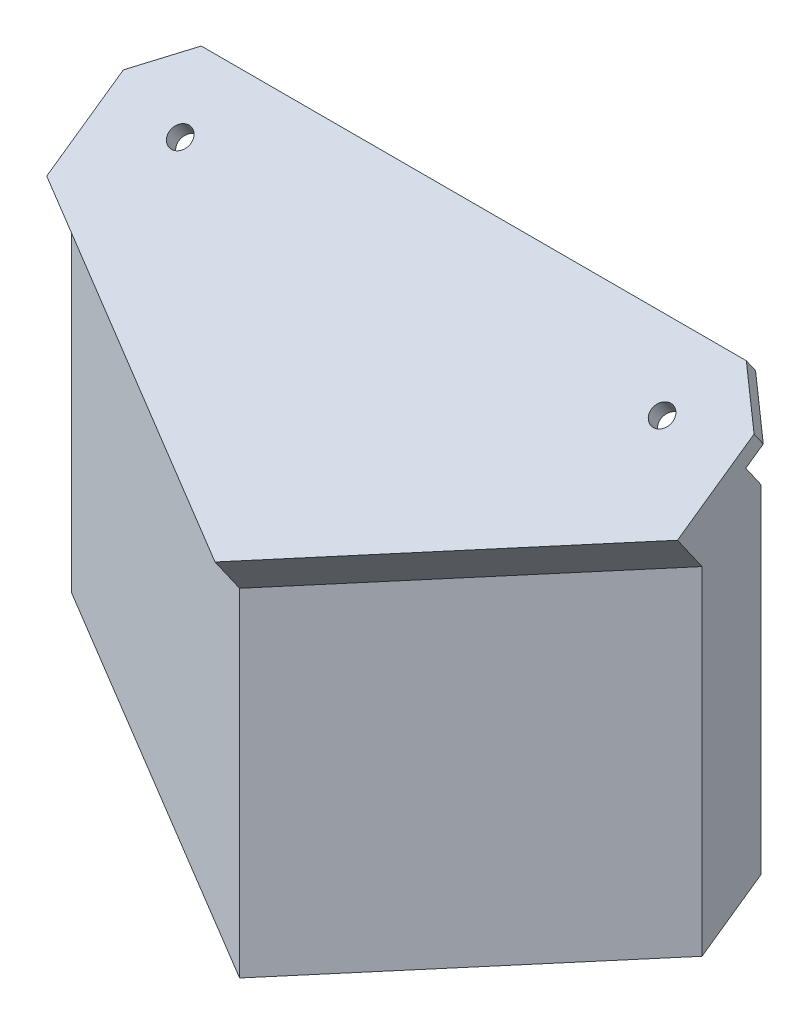
SolidWorks part; units mm, degrees
ref_plane "前视基准面" through (0, 0, 0) normal (0, 0, 1) x (1, 0, 0)
ref_plane "上视基准面" through (0, 0, 0) normal (0, 1, 0) x (1, 0, 0)
ref_plane "右视基准面" through (0, 0, 0) normal (1, 0, 0) x (0, 0, -1)
sketch "草图5" plane through (0, 0, 0) normal (0, 1, 0) x (1, 0, 0)
  line L0 (-58.91, 27.4702) -> (0, 0)
  line L1 (0, 0) -> (58.91, 27.4702)
  dimension "D1" = 65
  dimension "D2" = 130
extrude "拉伸-薄壁2" add sketch "草图5" along normal blind 90 thin
sketch "草图6" plane through (0, 0, 0) normal (1, 0, 0) x (0, 0, -1)
  line L0 (-11.0338, 0) -> (27.4702, 26.9608)
  line L1 (27.4702, 90) -> (27.4702, 0) construction
  line L2 (27.4702, 26.9608) -> (27.4702, 0)
  line L3 (27.4702, 0) -> (-11.0338, 0)
  line L4 (27.4702, 90) -> (-11.0338, 63.0392)
  line L5 (-11.0338, 90) -> (-11.0338, 0) construction
  line L6 (-11.0338, 63.0392) -> (-11.0338, 90)
  line L7 (-11.0338, 90) -> (27.4702, 90)
  dimension "D1" = 35
extrude "切除-拉伸1" cut sketch "草图6" against normal through all and the other way through all
sketch "草图7" plane through (0, 47.4841, 33.2488) normal (0, 0.8192, 0.5736) x (1, 0, 0)
  line L0 (63.1362, 63.0602) -> (58.91, 74.1241) construction
  line L1 (-58.91, 74.1241) -> (-63.1362, 63.0602) construction
  line L2 (63.1362, 63.0602) -> (0, 27.1195) construction
  line L3 (0, 27.1195) -> (-63.1362, 63.0602) construction
  line L4 (63.1362, 63.0602) -> (58.91, 74.1241)
  line L5 (-58.91, 74.1241) -> (-63.1362, 63.0602)
  line L6 (63.1362, 63.0602) -> (0, 27.1195)
  line L7 (0, 27.1195) -> (-63.1362, 63.0602)
  line L8 (-58.91, 74.1241) -> (-58.91, 94.1241)
  line L9 (58.91, 74.1241) -> (58.91, 94.1241)
  line L10 (58.91, 94.1241) -> (-58.91, 94.1241)
  dimension "D1" = 20
extrude "凸台-拉伸3" add sketch "草图7" along normal blind 8
sketch "草图8" plane through (0, 54.0374, 37.8374) normal (0, 0.8192, 0.5736) x (1, 0, 0)
  line L1 (-58.91, 94.1241) -> (58.91, 94.1241)
  line L2 (-58.91, 94.1241) -> (-58.91, -12.8388)
  line L3 (-58.91, -12.8388) -> (58.91, -12.8388)
  line L4 (58.91, 94.1241) -> (58.91, -12.8388)
extrude "切除-拉伸2" cut sketch "草图8" against normal through all flip side to cut
sketch "草图9" plane through (0, 47.4841, 33.2488) normal (0, -0.8192, -0.5736) x (1, 0, 0)
  line L0 (58.91, -94.1241) -> (-58.91, -94.1241) construction
  circle A0 centre (-45, -74.1241) radius 2
  circle A1 centre (45, -74.1241) radius 2
  dimension "D4" = 4
  dimension "D1" = 90
  dimension "D2" = 45
  dimension "D3" = 20
extrude "切除-拉伸3" cut sketch "草图9" against normal through all
sketch "草图10" plane through (0, 47.4841, 33.2488) normal (0, -0.8192, -0.5736) x (1, 0, 0)
  line L0 (58.91, -74.1241) -> (58.91, -94.1241) construction
  line L1 (-58.91, -94.1241) -> (58.91, -94.1241)
  line L2 (-58.91, -94.1241) -> (-58.91, -86.1241)
  line L3 (-58.91, -86.1241) -> (58.91, -86.1241)
  line L4 (58.91, -94.1241) -> (58.91, -86.1241)
  dimension "D1" = 8
extrude "切除-拉伸4" cut sketch "草图10" against normal blind 20
sketch "草图11" plane through (0, 47.4841, 33.2488) normal (0, -0.8192, -0.5736) x (1, 0, 0)
  line L8 (-58.91, -86.1241) -> (58.91, -86.1241)
  line L9 (58.91, -86.1241) -> (58.91, -74.1241)
  line L10 (58.91, -74.1241) -> (0, -40.5892)
  line L11 (0, -40.5892) -> (-58.91, -74.1241)
  line L12 (-58.91, -74.1241) -> (-58.91, -86.1241)
  line L13 (-58.91, -86.1241) -> (58.91, -86.1241)
  line L14 (58.91, -86.1241) -> (58.91, -74.1241)
  line L15 (58.91, -74.1241) -> (0, -40.5892)
  line L16 (0, -40.5892) -> (-58.91, -74.1241)
  line L17 (-58.91, -74.1241) -> (-58.91, -86.1241)
  dimension "D1" = 0
extrude "切除-拉伸6" cut sketch "草图11" against normal blind 5
chamfer "倒角1" distance 8 angle 45 2 edges at (58.91, 102.2074, -33.5718) (-58.91, 102.2074, -33.5718)
